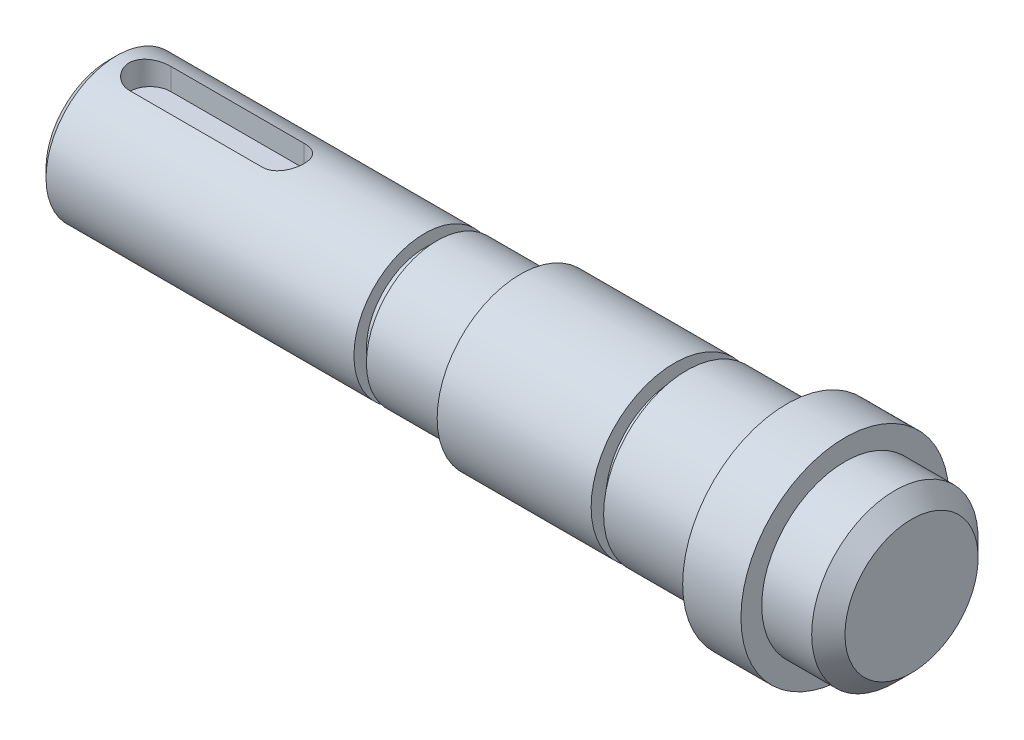
SolidWorks part; units mm, degrees
ref_plane "Plan1" through (0, 0, 0) normal (0, 0, 1) x (1, 0, 0)
ref_plane "Plan2" through (0, 0, 0) normal (0, 1, 0) x (1, 0, 0)
ref_plane "Plan3" through (0, 0, 0) normal (1, 0, 0) x (0, 0, -1)
sketch "Esquisse1" plane through (0, 0, 0) normal (0, 0, 1) x (1, 0, 0)
  line L0 (0, 0) -> (100, 0) construction
  line L1 (0, 0) -> (0, 7.5)
  line L2 (0, 7.5) -> (1, 8.5)
  line L3 (1, 8.5) -> (38, 8.5)
  line L4 (38, 8.5) -> (38, 7)
  line L5 (38, 7) -> (39.5, 7)
  line L6 (39.5, 7) -> (39.5, 8.5)
  line L7 (39.5, 8.5) -> (49.5, 8.5)
  line L8 (49.5, 8.5) -> (49.5, 10)
  line L9 (49.5, 10) -> (68, 10)
  line L10 (68, 10) -> (68, 8.25)
  line L11 (68, 8.25) -> (69.5, 8.25)
  line L12 (69.5, 8.25) -> (69.5, 10)
  line L13 (69.5, 10) -> (81.5, 10)
  line L14 (81.5, 10) -> (81.5, 12.5)
  line L15 (81.5, 12.5) -> (88.5, 12.5)
  line L16 (88.5, 12.5) -> (88.5, 10)
  line L17 (88.5, 10) -> (94.5, 10)
  line L18 (94.5, 10) -> (96.5, 8)
  line L19 (96.5, 8) -> (96.5, 0)
  line L20 (0, 0) -> (96.5, 0)
  dimension "D1" = 45
  dimension "D2" = 1
  dimension "D3" = 17
  dimension "D4" = 38
  dimension "D5" = 1.5
  dimension "D6" = 14
  dimension "D7" = 10
  dimension "D8" = 18.5
  dimension "D9" = 20
  dimension "D10" = 1.5
  dimension "D11" = 16.5
  dimension "D12" = 12
  dimension "D13" = 7
  dimension "D14" = 25
  dimension "D15" = 45
  dimension "D16" = 2
  dimension "D17" = 8
revolve "Base-Révolution" add sketch "Esquisse1" angle 360 about L0
ref_plane "Plan4" through (0, 10, 0) normal (0, 1, 0) x (-1, 0, 0)
sketch "Esquisse2" plane through (0, 10, 0) normal (0, 1, 0) x (-1, 0, 0)
  line L0 (0, 0) -> (-24.1, 0) construction
  line L1 (-21, 2.5) -> (-5, 2.5)
  line L2 (-21, -2.5) -> (-5, -2.5)
  arc A0 (-5, -2.5) -> (-5, 2.5) centre (-5, 0) ccw
  arc A1 (-21, 2.5) -> (-21, -2.5) centre (-21, 0) ccw
  dimension "D1" = 2.5
  dimension "D2" = 2.5
  dimension "D3" = 5
  dimension "D4" = 16
extrude "Enlèv. mat.-Extru.1" cut sketch "Esquisse2" against normal blind 4.5
